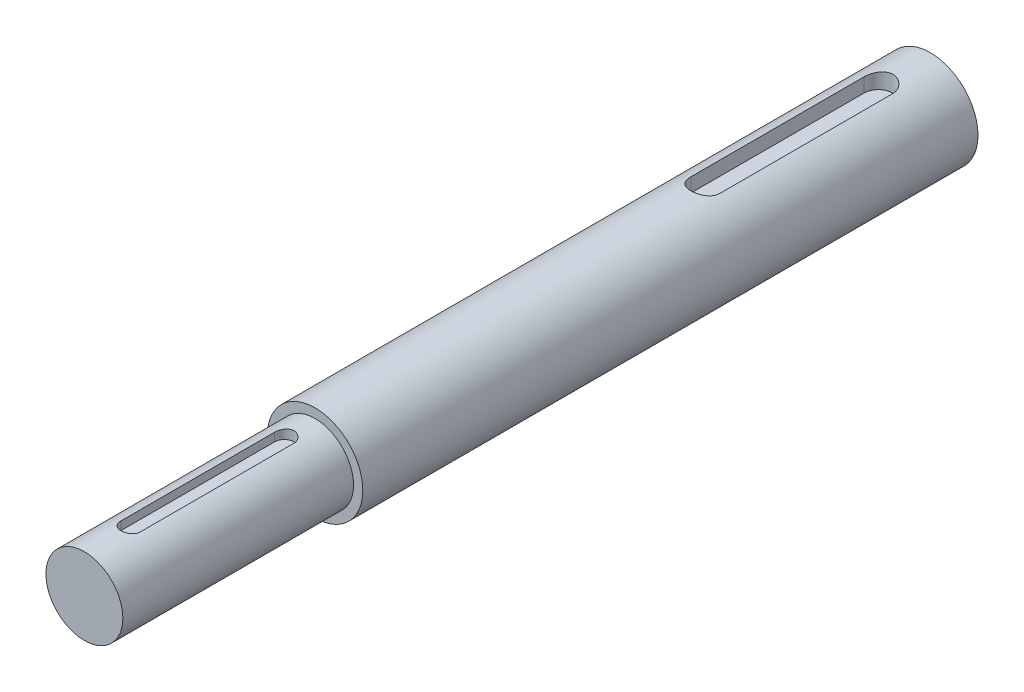
SolidWorks part; units mm, degrees
ref_plane "Front Plane" through (0, 0, 0) normal (0, 0, 1) x (1, 0, 0)
ref_plane "Top Plane" through (0, 0, 0) normal (0, 1, 0) x (1, 0, 0)
ref_plane "Right Plane" through (0, 0, 0) normal (1, 0, 0) x (0, 0, -1)
sketch "Sketch1" plane through (0, 0, 0) normal (0, 0, 1) x (1, 0, 0)
  circle A0 centre (0, 0) radius 7.874
extrude "Boss-Extrude1" add sketch "Sketch1" along normal blind 101.6
sketch "Sketch2" plane through (0, 0, 101.6) normal (0, 0, 1) x (1, 0, 0)
  circle A0 centre (0, 0) radius 6.35
extrude "Boss-Extrude2" add sketch "Sketch2" along normal blind 38.1
sketch "Sketch4" plane through (0, 0, 139.7) normal (0, 0, 1) x (1, 0, 0)
  circle A0 centre (0, 0) radius 6.35 construction
  circle A1 centre (0, 0) radius 6.35 construction
  point P0 (0, 6.35)
ref_plane "Plane2" through (0, 6.35, 139.7) normal (0, 1, 0) x (1, 0, 0)
sketch "Sketch6" plane through (0, 6.35, 139.7) normal (0, 1, 0) x (1, 0, 0)
  line L0 (0, 33.02) -> (0, 7.62) construction
  line L1 (1.5875, 33.02) -> (1.5875, 7.62)
  line L2 (-1.5875, 33.02) -> (-1.5875, 7.62)
  line L5 (-7.874, 38.1) -> (7.874, 38.1) construction
  arc A0 (1.5875, 33.02) -> (-1.5875, 33.02) centre (0, 33.02) ccw
  arc A1 (-1.5875, 7.62) -> (1.5875, 7.62) centre (0, 7.62) ccw
  point P3 (0, 20.32)
  dimension "D1" = 17.78
sketch "Sketch7" plane through (0, 6.35, 139.7) normal (0, 1, 0) x (1, 0, 0)
  line L0 (0, 131.1275) -> (0, 102.5525) construction
  line L1 (2.3876, 131.1275) -> (2.3876, 102.5525)
  line L2 (-2.3876, 131.1275) -> (-2.3876, 102.5525)
  line L4 (7.874, 139.7) -> (-7.874, 139.7) construction
  arc A0 (2.3876, 131.1275) -> (-2.3876, 131.1275) centre (0, 131.1275) ccw
  arc A1 (-2.3876, 102.5525) -> (2.3876, 102.5525) centre (0, 102.5525) ccw
  point P3 (0, 116.84)
  dimension "D1" = 22.86
extrude "Cut-Extrude3" cut sketch "Sketch6" against normal blind 1.5875
extrude "Cut-Extrude5" cut sketch "Sketch7" along normal blind 1.524 and the other way blind 1.1684
